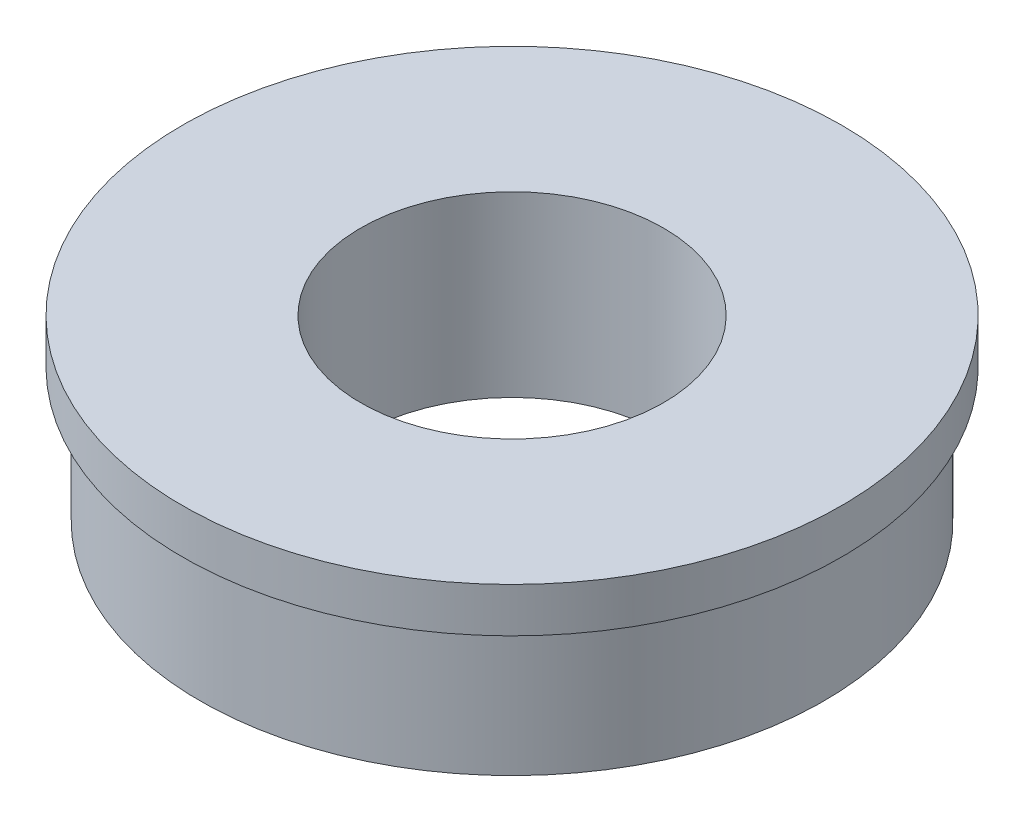
SolidWorks part; units mm, degrees
ref_plane "前视基准面" through (0, 0, 0) normal (0, 0, 1) x (1, 0, 0)
ref_plane "上视基准面" through (0, 0, 0) normal (0, 1, 0) x (1, 0, 0)
ref_plane "右视基准面" through (0, 0, 0) normal (1, 0, 0) x (0, 0, -1)
sketch "Sketch1" plane through (0, 0, 0) normal (0, 0, 1) x (1, 0, 0)
  line L0 (8.5, 0) -> (18.5, 0)
  line L1 (18.5, 0) -> (18.5, -2.5)
  line L2 (18.5, -2.5) -> (17.5, -2.5)
  line L3 (17.5, -2.5) -> (17.5, -10)
  line L4 (17.5, -10) -> (8.5, -10)
  line L5 (8.5, -10) -> (8.5, 0)
  line L6 (0, -7.3784) -> (0, 8.2134) construction
  dimension "D1" = 8.5
  dimension "D2" = 17.5
  dimension "D3" = 2.5
  dimension "D4" = 10
  dimension "D5" = 18.5
revolve "Revolve1" add sketch "Sketch1" angle 360 about L6
